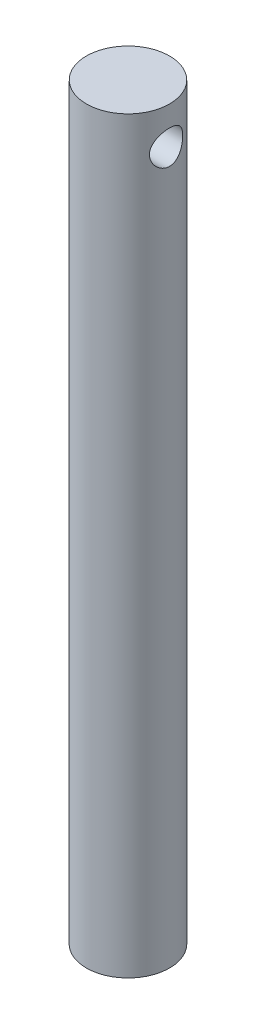
SolidWorks part; units mm, degrees
ref_plane "Front Plane" through (0, 0, 0) normal (0, 0, 1) x (1, 0, 0)
ref_plane "Top Plane" through (0, 0, 0) normal (0, 1, 0) x (1, 0, 0)
ref_plane "Right Plane" through (0, 0, 0) normal (1, 0, 0) x (0, 0, -1)
sketch "Sketch1" plane through (0, 0, 0) normal (0, 1, 0) x (1, 0, 0)
  circle A0 centre (0, 0) radius 10
  dimension "D1" = 20
extrude "Boss-Extrude1" add sketch "Sketch1" along normal blind 180
sketch "Sketch2" plane through (0, 0, 0) normal (1, 0, 0) x (0, 0, -1)
  line L0 (10, 180) -> (-10, 180) construction
  circle A0 centre (0, 171) radius 4
  dimension "D1" = 8
  dimension "D2" = 9
extrude "Cut-Extrude1" cut sketch "Sketch2" against normal through all both and the other way through all
